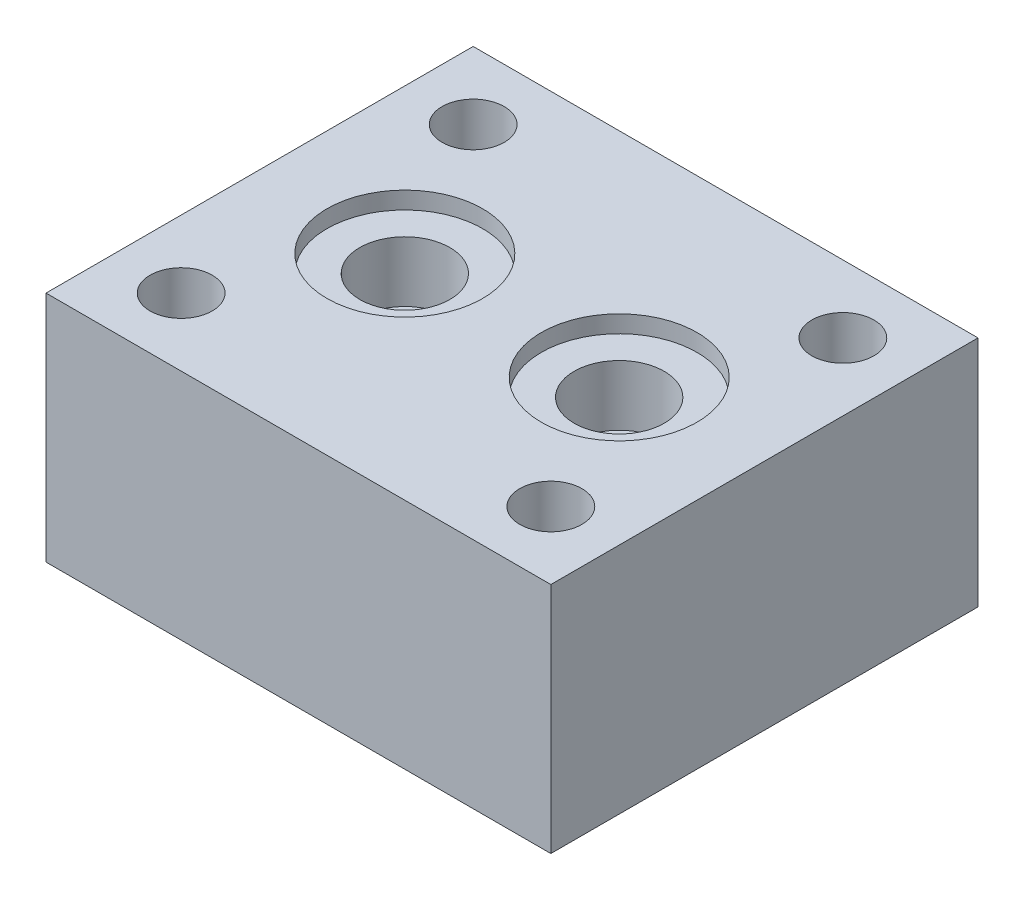
SolidWorks part; units mm, degrees
ref_plane "Front Plane" through (0, 0, 0) normal (0, 0, 1) x (1, 0, 0)
ref_plane "Top Plane" through (0, 0, 0) normal (0, 1, 0) x (1, 0, 0)
ref_plane "Right Plane" through (0, 0, 0) normal (1, 0, 0) x (0, 0, -1)
sketch "Sketch1" plane through (0, 0, 0) normal (0, 1, 0) x (1, 0, 0)
  line L1 (-41.275, -34.925) -> (41.275, -34.925)
  line L2 (-41.275, -34.925) -> (-41.275, 34.925)
  line L3 (-41.275, 34.925) -> (41.275, 34.925)
  line L4 (41.275, -34.925) -> (41.275, 34.925)
  line L5 (-41.275, -34.925) -> (41.275, 34.925) construction
  line L6 (-41.275, 34.925) -> (41.275, -34.925) construction
  point P0 (0, 0)
  dimension "D1" = 41.275
  dimension "D2" = 34.925
extrude "Boss-Extrude1" add sketch "Sketch1" along normal mid plane 38.1
sketch "Sketch2" plane through (0, 0, 0) normal (0, 1, 0) x (1, 0, 0)
  circle A0 centre (-30.226, -23.876) radius 5.08
  circle A1 centre (30.226, -23.876) radius 5.08
  circle A2 centre (-30.226, 23.876) radius 5.08
  circle A3 centre (30.226, 23.876) radius 5.08
  point P8 (0, 0)
  dimension "D1" = 10.16
  dimension "D2" = 10.16
  dimension "D3" = 10.16
  dimension "D4" = 10.16
  dimension "D5" = 60.452
  dimension "D6" = 47.752
  dimension "D7" = 30.226
  dimension "D8" = 23.876
extrude "Cut-Extrude2" cut sketch "Sketch2" against normal through all from offset 19.05
sketch "Sketch3" plane through (0, 0, 0) normal (0, 1, 0) x (1, 0, 0)
  circle A0 centre (-17.526, 0) radius 7.366
  circle A1 centre (17.526, 0) radius 7.366
  point P4 (0, 0)
  dimension "D1" = 14.732
  dimension "D2" = 14.732
  dimension "D3" = 35.052
  dimension "D4" = 17.526
extrude "Cut-Extrude4" cut sketch "Sketch3" against normal blind 12.7 from offset 19.05
sketch "Sketch4" plane through (0, 0, 0) normal (0, 1, 0) x (1, 0, 0)
  circle A0 centre (-17.526, 0) radius 12.7254
  circle A1 centre (17.526, 0) radius 12.7254
  point P4 (0, 0)
  dimension "D1" = 25.4508
  dimension "D2" = 25.4508
  dimension "D3" = 35.052
  dimension "D4" = 17.526
extrude "Cut-Extrude6" cut sketch "Sketch4" against normal blind 2.8194 from offset 19.05
